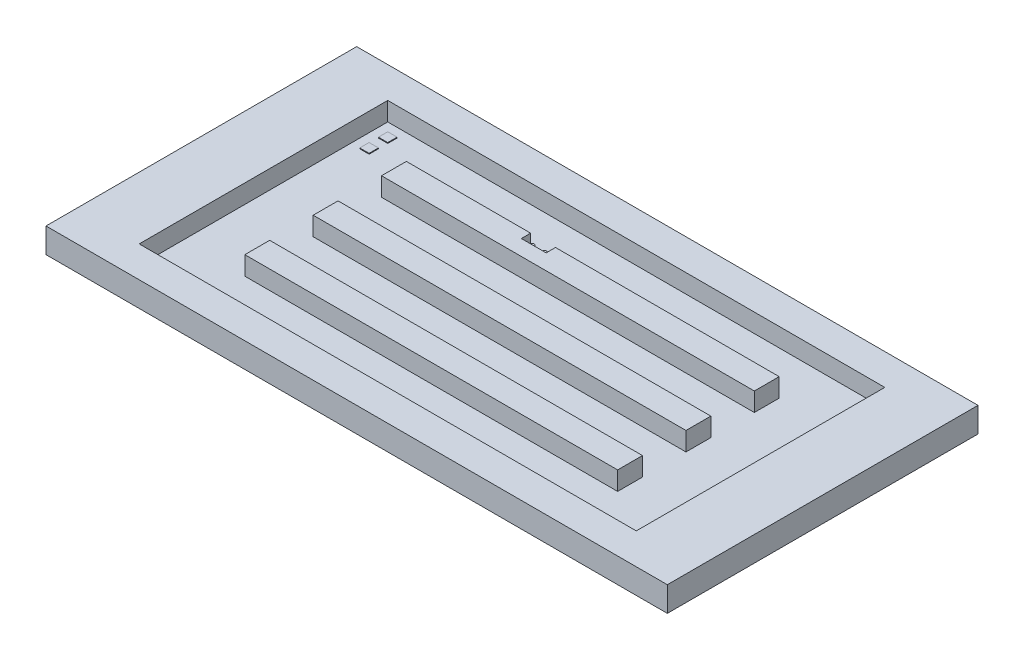
SolidWorks part; units mm, degrees
ref_plane "前基準面" through (0, 0, 0) normal (0, 0, 1) x (1, 0, 0)
ref_plane "上基準面" through (0, 0, 0) normal (0, 1, 0) x (1, 0, 0)
ref_plane "右基準面" through (0, 0, 0) normal (1, 0, 0) x (0, 0, -1)
sketch "草圖1" plane through (0, 0, 0) normal (0, 1, 0) x (1, 0, 0)
  line L1 (-5000, 2500) -> (5000, 2500)
  line L2 (-5000, 2500) -> (-5000, -2500)
  line L3 (-5000, -2500) -> (5000, -2500)
  line L4 (5000, 2500) -> (5000, -2500)
  line L5 (-5000, 2500) -> (5000, -2500) construction
  line L6 (-5000, -2500) -> (5000, 2500) construction
  point P0 (0, 0)
  dimension "D1" = 10000
  dimension "D2" = 5000
extrude "伸長1" add sketch "草圖1" along normal blind 400
sketch "草圖2" plane through (0, 400, 0) normal (0, 1, 0) x (1, 0, 0)
  line L1 (4000, 2000) -> (-4000, 2000)
  line L2 (4000, 2000) -> (4000, -2000)
  line L3 (4000, -2000) -> (-4000, -2000)
  line L4 (-4000, 2000) -> (-4000, -2000)
  line L5 (4000, 2000) -> (-4000, -2000) construction
  line L6 (4000, -2000) -> (-4000, 2000) construction
  line L7 (-3000, 1300) -> (3000, 1300)
  line L8 (-3000, 1300) -> (-3000, 900)
  line L9 (-3000, 900) -> (3000, 900)
  line L10 (3000, 1300) -> (3000, 900)
  line L11 (3000, 200) -> (-3000, 200)
  line L12 (3000, 200) -> (3000, -200)
  line L13 (3000, -200) -> (-3000, -200)
  line L14 (-3000, 200) -> (-3000, -200)
  line L15 (-3000, -900) -> (3000, -900)
  line L16 (-3000, -900) -> (-3000, -1300)
  line L17 (-3000, -1300) -> (3000, -1300)
  line L18 (3000, -900) -> (3000, -1300)
  point P0 (0, 0)
  dimension "D1" = 8000
  dimension "D2" = 4000
  dimension "D3" = 700
  dimension "D4" = 700
  dimension "D5" = 700
  dimension "D6" = 700
  dimension "D7" = 400
  dimension "D8" = 400
  dimension "D9" = 1000
  dimension "D10" = 1000
extrude "伸長2" cut sketch "草圖2" against normal blind 300
sketch "草圖3" plane through (0, 400, 0) normal (0, 1, 0) x (1, 0, 0)
  line L0 (3000, 1300) -> (-3000, 1300) construction
  line L1 (-1000, 1300) -> (-600, 1300)
  line L2 (-1000, 1300) -> (-1000, 1150)
  line L3 (-1000, 1150) -> (-600, 1150)
  line L4 (-600, 1300) -> (-600, 1150)
  line L5 (-3000, 1300) -> (-3000, 900) construction
  dimension "D1" = 2000
  dimension "D2" = 400
  dimension "D3" = 150
sketch "草圖4" plane through (0, 100, 0) normal (0, 1, 0) x (1, 0, 0)
  line L0 (4000, 2000) -> (-4000, 2000) construction
  line L1 (-3850, 1850) -> (-3700, 1850)
  line L2 (-3850, 1850) -> (-3850, 1700)
  line L3 (-3850, 1700) -> (-3700, 1700)
  line L4 (-3700, 1850) -> (-3700, 1700)
  line L5 (-3700, 1550) -> (-3850, 1550)
  line L6 (-3700, 1550) -> (-3700, 1400)
  line L7 (-3700, 1400) -> (-3850, 1400)
  line L8 (-3850, 1550) -> (-3850, 1400)
  line L10 (-4000, 2000) -> (-4000, -2000) construction
  dimension "D1" = 150
  dimension "D2" = 150
  dimension "D3" = 150
  dimension "D4" = 150
  dimension "D5" = 150
  dimension "D6" = 150
extrude "伸長3" add sketch "草圖4" along normal blind 13
extrude "伸長4" cut sketch "草圖3" against normal blind 200
sketch "草圖5" plane through (0, 200, 0) normal (0, 1, 0) x (1, 0, 0)
  line L0 (-1000, 1300) -> (-1000, 1150) construction
  line L1 (-900, 1221.987) -> (-700, 1221.987) construction
  circle A0 centre (-900, 1221.987) radius 33
  circle A1 centre (-700, 1221.987) radius 33
  dimension "D2" = 66
  dimension "D3" = 66
  dimension "D1" = 200
  dimension "D4" = 100
extrude "伸長5" add sketch "草圖5" along normal blind 123
